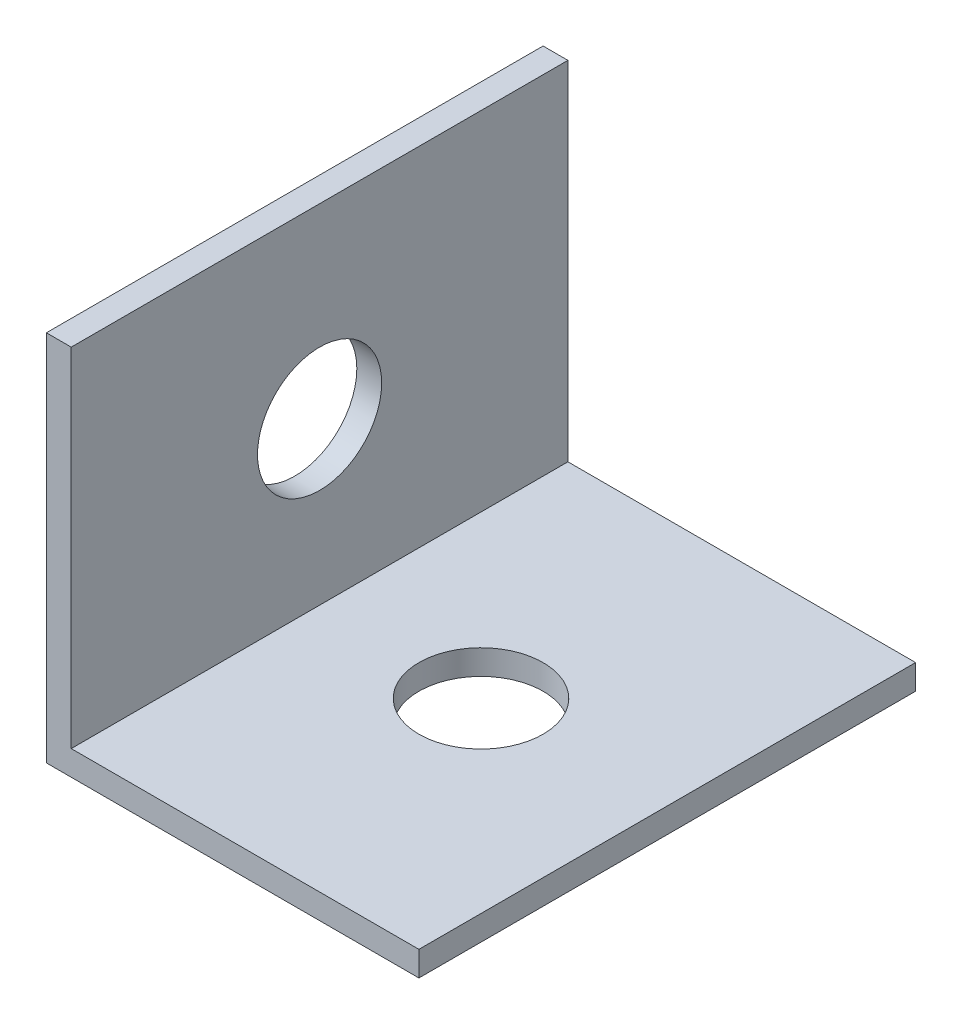
SolidWorks part; units mm, degrees
material "Alloy Steel"
ref_plane "Front Plane" through (0, 0, 0) normal (0, 0, 1) x (1, 0, 0)
ref_plane "Top Plane" through (0, 0, 0) normal (0, 1, 0) x (1, 0, 0)
ref_plane "Right Plane" through (0, 0, 0) normal (1, 0, 0) x (0, 0, -1)
sketch "Sketch1" plane through (0, 0, 0) normal (0, 0, 1) x (1, 0, 0)
  line L0 (0, 0) -> (0, 38.1)
  line L1 (0, 38.1) -> (2.54, 38.1)
  line L2 (2.54, 38.1) -> (2.54, 2.54)
  line L3 (2.54, 2.54) -> (38.1, 2.54)
  line L4 (38.1, 2.54) -> (38.1, 0)
  line L5 (38.1, 0) -> (0, 0)
  dimension "D1" = 2.54
  dimension "D2" = 2.54
  dimension "D3" = 38.1
  dimension "D4" = 38.1
extrude "Boss-Extrude1" add sketch "Sketch1" along normal blind 50.8
hole_wizard "#97 (0.5) Diameter Hole1" positions "3DSketch2" profile "Sketch3" hole size "#97" standard "ANSI Inch" end condition through all
sketch3d "3DSketch2"
  line L0 (2.54, 38.1, 50.8) -> (2.54, 38.1, 0) construction
  line L1 (2.54, 2.54, 50.8) -> (2.54, 38.1, 50.8) construction
  point P0 (2.54, 19.05, 25.4)
  dimension "D1" = 19.05
  dimension "D2" = 25.4
sketch "Sketch3" plane through (2.54, 19.05, 25.4) normal (0, 1, 0) x (0, 0, -1)
  line L0 (0, 0) -> (0, 2.54)
  line L1 (0, 2.54) -> (6.35, 2.54)
  line L2 (6.35, 2.54) -> (6.35, 0)
  line L5 (6.35, 0) -> (0, 0)
  line L11 (0, -6.35) -> (0, 107.95) construction
  dimension "Thru Hole Dia." = 12.7
  dimension "Thru Hole Depth" = 2.54
hole_wizard "#97 (0.5) Diameter Hole2" positions "Sketch4" profile "Sketch5" hole size "#97" standard "ANSI Inch" end condition through all
sketch "Sketch4" plane through (0, 2.54, 0) normal (0, 1, 0) x (1, 0, 0)
  line L0 (38.1, 0) -> (2.54, 0) construction
  line L1 (38.1, -50.8) -> (38.1, 0) construction
  point P0 (19.05, -25.4)
  dimension "D1" = 25.4
  dimension "D2" = 19.05
sketch "Sketch5" plane through (19.05, 2.54, 25.4) normal (1, 0, 0) x (0, 0, 1)
  line L0 (0, 0) -> (0, 2.54)
  line L1 (0, 2.54) -> (6.35, 2.54)
  line L2 (6.35, 2.54) -> (6.35, 0)
  line L5 (6.35, 0) -> (0, 0)
  line L11 (0, -6.35) -> (0, 107.95) construction
  dimension "Thru Hole Dia." = 12.7
  dimension "Thru Hole Depth" = 2.54
